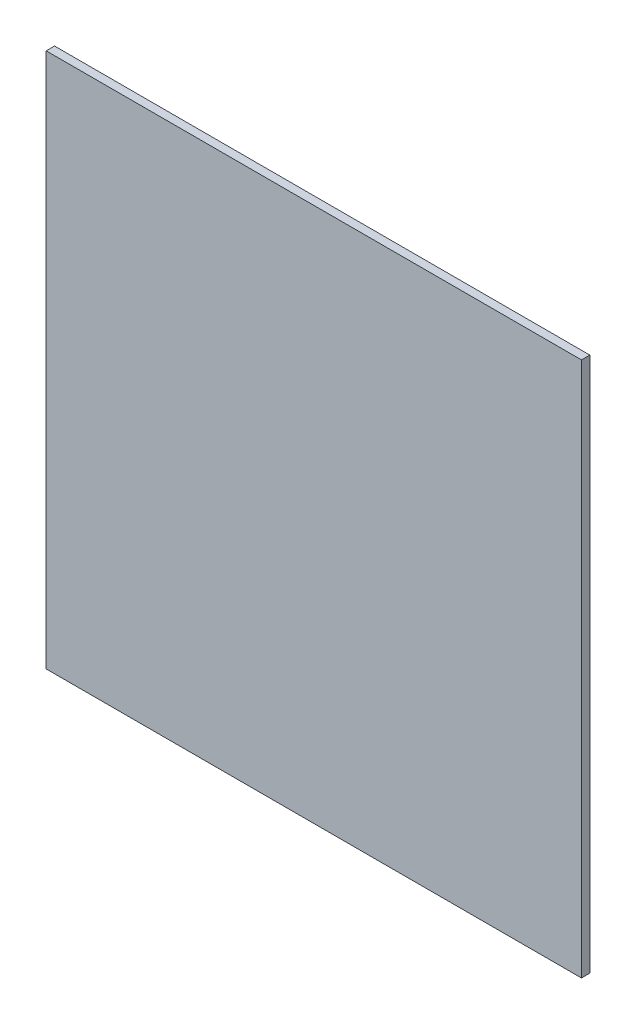
SolidWorks part; units mm, degrees
ref_plane "Front Plane" through (0, 0, 0) normal (0, 0, 1) x (1, 0, 0)
ref_plane "Top Plane" through (0, 0, 0) normal (0, 1, 0) x (1, 0, 0)
ref_plane "Right Plane" through (0, 0, 0) normal (1, 0, 0) x (0, 0, -1)
sketch "Sketch1" plane through (0, 0, 0) normal (0, 0, 1) x (1, 0, 0)
  line L1 (-609.6, 609.6) -> (609.6, 609.6)
  line L2 (-609.6, 609.6) -> (-609.6, -609.6)
  line L3 (-609.6, -609.6) -> (609.6, -609.6)
  line L4 (609.6, 609.6) -> (609.6, -609.6)
  line L5 (-609.6, 609.6) -> (609.6, -609.6) construction
  line L6 (-609.6, -609.6) -> (609.6, 609.6) construction
  point P0 (0, 0)
  dimension "D1" = 1219.2
  dimension "D2" = 1219.2
extrude "Boss-Extrude1" add sketch "Sketch1" along normal blind 19.05
